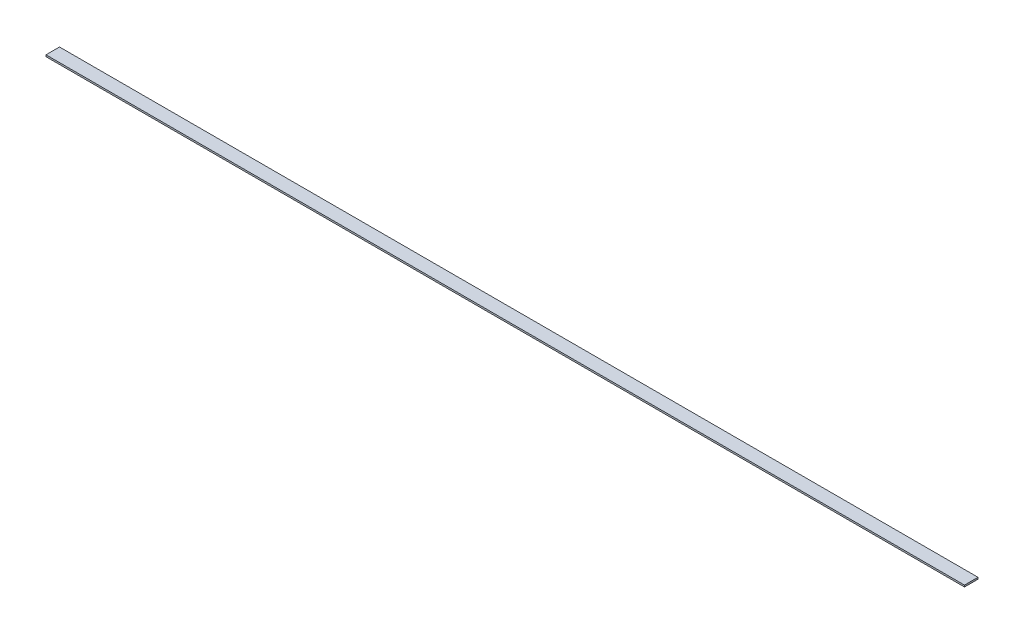
SolidWorks part; units mm, degrees
material "Polyurethane Foam Flexible"
ref_plane "Front Plane" through (0, 0, 0) normal (0, 0, 1) x (1, 0, 0)
ref_plane "Top Plane" through (0, 0, 0) normal (0, 1, 0) x (1, 0, 0)
ref_plane "Right Plane" through (0, 0, 0) normal (1, 0, 0) x (0, 0, -1)
sketch "Sketch1" plane through (0, 0, 0) normal (0, 1, 0) x (1, 0, 0)
  line L1 (-863.6, -12.7) -> (863.6, -12.7)
  line L2 (-863.6, -12.7) -> (-863.6, 12.7)
  line L3 (-863.6, 12.7) -> (863.6, 12.7)
  line L4 (863.6, -12.7) -> (863.6, 12.7)
  line L5 (-863.6, -12.7) -> (863.6, 12.7) construction
  line L6 (-863.6, 12.7) -> (863.6, -12.7) construction
  point P0 (0, 0)
  dimension "D1" = 25.4
  dimension "D2" = 1727.2
extrude "Boss-Extrude1" add sketch "Sketch1" along normal blind 3.175
